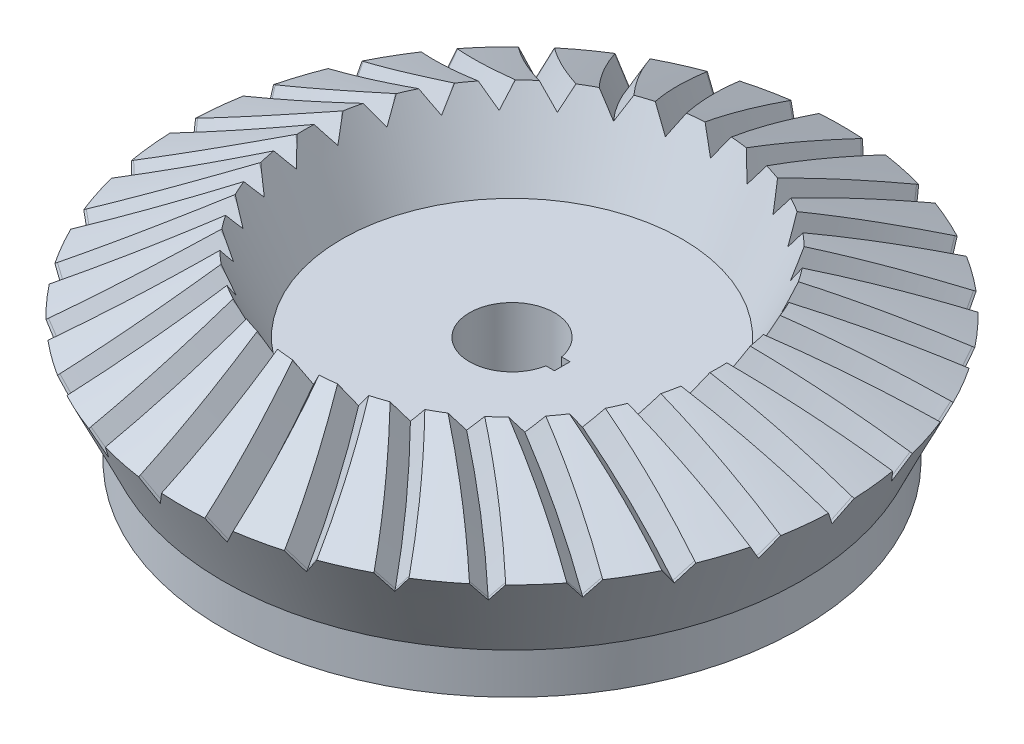
SolidWorks part; units mm, degrees
ref_plane "Alzado" through (0, 0, 0) normal (0, 0, 1) x (1, 0, 0)
ref_plane "Planta" through (0, 0, 0) normal (0, 1, 0) x (1, 0, 0)
ref_plane "Vista lateral" through (0, 0, 0) normal (1, 0, 0) x (0, 0, -1)
sketch "Croquis1" plane through (0, 0, 0) normal (0, 0, 1) x (1, 0, 0)
  line L0 (0, 0) -> (0, 40)
  line L1 (0, 40) -> (50, 40)
  line L2 (50, 40) -> (60.7108, 62.5894)
  line L3 (60.7108, 62.5894) -> (96.8537, 45.4522)
  line L4 (96.8537, 45.4522) -> (85, 20.4522)
  line L5 (85, 20.4522) -> (85, 8.4522)
  line L6 (85, 8.4522) -> (20, 8.4522)
  line L7 (20, 8.4522) -> (20, 0)
  line L8 (20, 0) -> (0, 0)
  line L9 (0, 0) -> (0, 72.7393) construction
  dimension "D1" = 40
  dimension "D2" = 50
  dimension "D3" = 25
  dimension "D4" = 40
  dimension "D5" = 25
  dimension "D6" = 65
  dimension "D7" = 20
  dimension "D8" = 12
  dimension "D9" = 115.368
  dimension "D10" = 90
revolve "Revolución1" add sketch "Croquis1" angle 360 about L9
ref_plane "Plano1" through (-61.4806, -29.151, 0) normal (-0.9036, -0.4284, 0) x (0, 0, 1)
sketch "Croquis2" plane through (-61.4806, -29.151, 0) normal (-0.9036, -0.4284, 0) x (0, 0, 1)
  line L0 (0, 82.5645) -> (0, 69.4382) construction
  line L1 (0, 76.0014) -> (3.9, 82.7563)
  line L2 (3.9, 82.7563) -> (-3.9, 82.7563)
  line L3 (-3.9, 82.7563) -> (0, 76.0014)
  ellipse E0 centre (0, 41.0694) end of major axis (-96.8537, 41.0694) minor radius 41.4951 construction
  dimension "D1" = 7.8
  dimension "D2" = 7.8
  dimension "D3" = 7.8
ref_plane "Plano3" through (-35.3731, 74.6032, 0) normal (-0.4284, 0.9036, 0) x (0.9036, 0.4284, 0)
sketch "Croquis6" plane through (-35.3731, 74.6032, 0) normal (-0.4284, 0.9036, 0) x (0.9036, 0.4284, 0)
  line L0 (-68.0415, 1.95) -> (-67.3859, 2.0112)
  line L1 (-68.0415, 3.9) -> (-68.0415, 0) construction
  line L2 (-27.3372, 8.5031) -> (-26.7842, 8.6316)
  arc A0 (-67.3859, 2.0112) -> (-27.3372, 8.5031) centre (-95.2553, 300.7139) ccw
  point P7 (-47.1415, 3.9)
  dimension "D2" = 300
  dimension "D1" = 20.9
sweep "Cortar-Barrer2" cut profiles "Croquis2" path "Croquis6"
pattern_circular "MatrizC3" count 30 over 360 about axis through (0, 45.4522, 0) along (0, -1, 0) of "Cortar-Barrer2"
sketch "Croquis7" plane through (0, 0, 0) normal (0, -1, 0) x (1, 0, 0)
  line L1 (12.2874, -2.2956) -> (14.7669, -2.2956)
  line L3 (12.2874, 2.2956) -> (14.7669, 2.2956)
  line L4 (14.7669, -2.2956) -> (14.7669, 2.2956)
  circle A0 centre (0, 0) radius 20
  arc A1 (12.2874, 2.2956) -> (12.2874, -2.2956) centre (0, 0) ccw
  point P4 (12.5, 0)
extrude "Cortar-Extruir3" cut sketch "Croquis7" against normal blind 150 contours A1 L1 L4 L3
